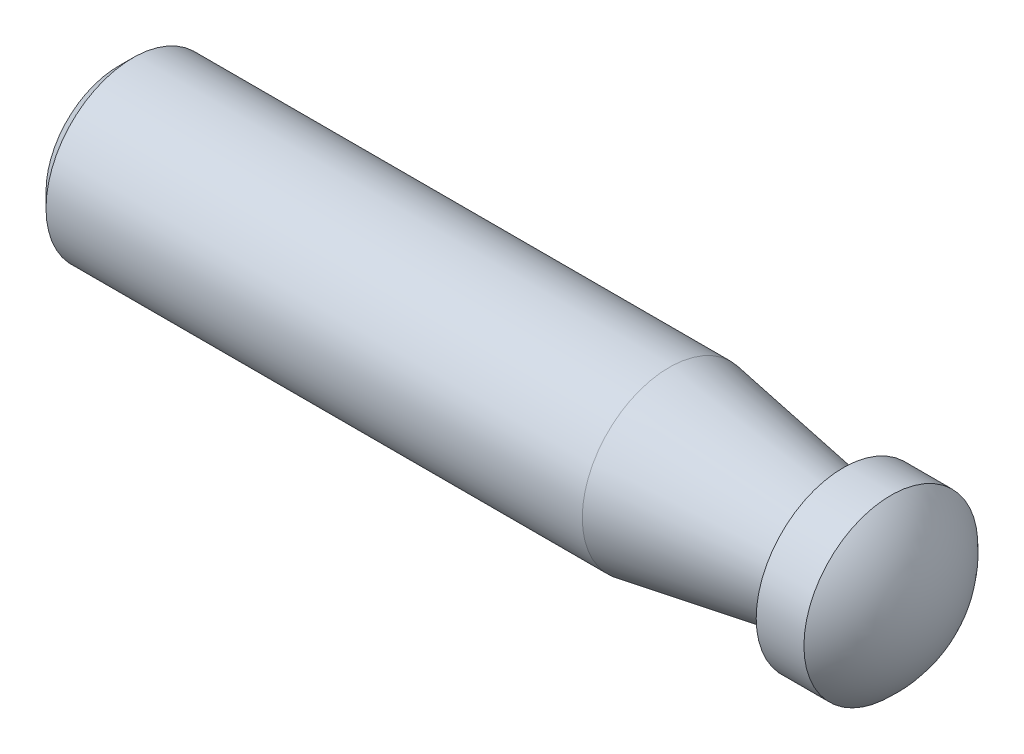
SolidWorks part; units mm, degrees
ref_plane "Plan1" through (0, 0, 0) normal (0, 0, 1) x (1, 0, 0)
ref_plane "Plan2" through (0, 0, 0) normal (0, 1, 0) x (1, 0, 0)
ref_plane "Plan3" through (0, 0, 0) normal (1, 0, 0) x (0, 0, -1)
sketch "Esquisse1" plane through (0, 0, 0) normal (0, 0, 1) x (1, 0, 0)
  line L0 (0, 0) -> (28, 0) construction
  line L1 (0, 0) -> (0, 3)
  line L2 (0, 3) -> (19, 3)
  line L3 (0, 0) -> (28, 0)
  line L4 (25, 3) -> (25, 2)
  line L5 (25, 3) -> (26.6458, 3)
  line L6 (19, 3) -> (25, 2)
  arc A1 (28, 0) -> (26.6458, 3) centre (24, 0) ccw
  dimension "D2" = 3
  dimension "D6" = 4
  dimension "D1" = 28
  dimension "D3" = 19
  dimension "D4" = 6
  dimension "D5" = 1
revolve "Base-Révolution" add sketch "Esquisse1" angle 360 about L0
chamfer "Chanfrein1" distance 0.5 angle 45
sketch "Esquisse2" plane through (0, 0, 0) normal (0, 1, 0) x (1, 0, 0)
  line L0 (0.5, 0) -> (0, 0) construction
  point P0 (24, 0)
  dimension "D1" = 24
